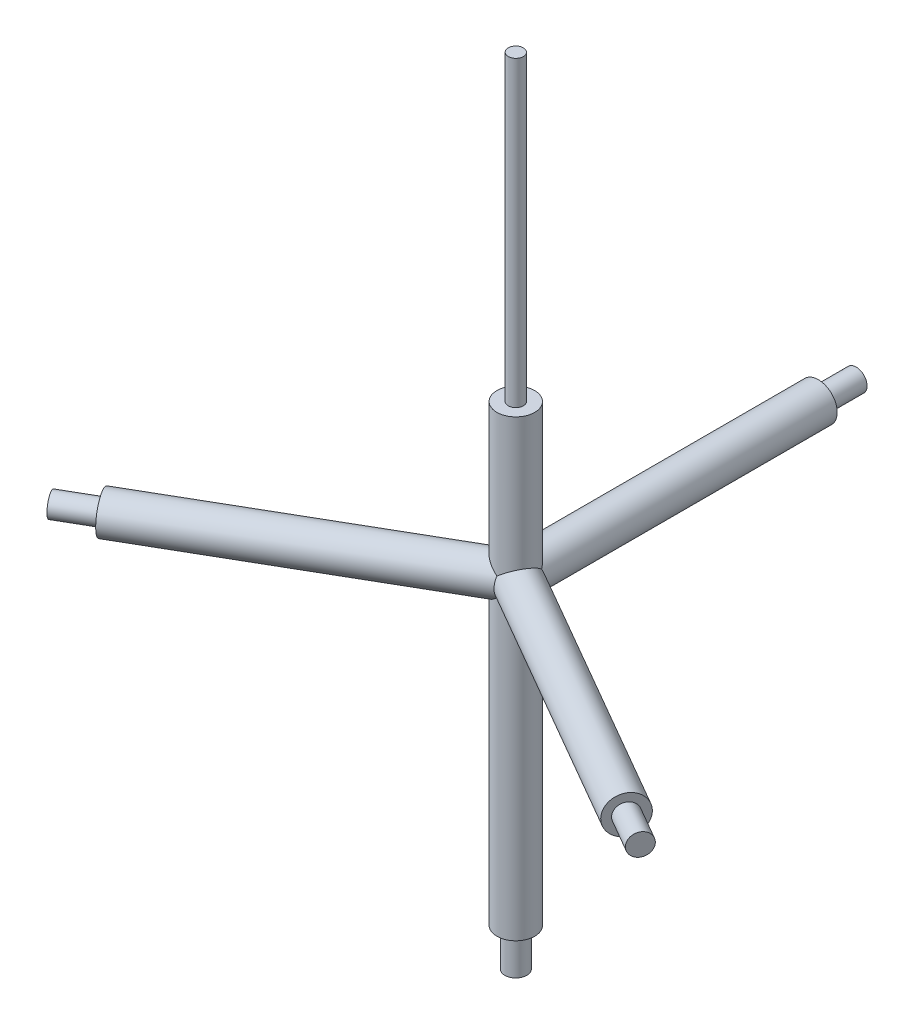
SolidWorks part; units mm, degrees
other "相机1"
ref_plane "前视基准面" through (0, 0, 0) normal (0, 0, 1) x (1, 0, 0)
ref_plane "上视基准面" through (0, 0, 0) normal (0, 1, 0) x (1, 0, 0)
ref_plane "右视基准面" through (0, 0, 0) normal (1, 0, 0) x (0, 0, -1)
sketch "草图1" plane through (0, 0, 0) normal (0, 1, 0) x (1, 0, 0)
  line L0 (0, 0) -> (0, 40)
  dimension "D4" = 40
revolve "杆件1" add sketch "草图1" angle 360 about L0 wall 2.5
sketch "草图8" plane through (0, 0, -40) normal (0, 0, -1) x (-1, 0, 0)
  circle A0 centre (0, 0) radius 1.45
  dimension "D1" = 2.9
extrude "凸台-拉伸2" add sketch "草图8" along normal blind 5
sketch "旋转轴" plane through (0, 0, 0) normal (0, 0, 1) x (1, 0, 0)
  line L0 (0, -1000) -> (0, 49000) construction
pattern_circular "阵列(圆周)杆件" count 3 over 360 about axis through (0, 0, 0) along (0, 1, 0) of "杆件1"
sketch "草图5" plane through (0, 0, 0) normal (0, 1, 0) x (1, 0, 0)
  circle A0 centre (0, 0) radius 2.5
  dimension "D1" = 5
extrude "杆件2" add sketch "草图5" along normal blind 20 and the other way blind 40
sketch "草图6" plane through (0, 20, 0) normal (0, 1, 0) x (1, 0, 0)
  circle A0 centre (0, 0) radius 1
  dimension "D1" = 2
extrude "凸台-拉伸1" add sketch "草图6" along normal blind 40
pattern_circular "阵列(圆周)1" count 3 over 360 about axis through (0, 0, 0) along (0, 1, 0) of "凸台-拉伸2"
sketch "草图9" plane through (0, -40, 0) normal (0, -1, 0) x (1, 0, 0)
  circle A0 centre (0, 0) radius 1.45
  dimension "D1" = 2.9
extrude "凸台-拉伸3" add sketch "草图9" along normal blind 5
